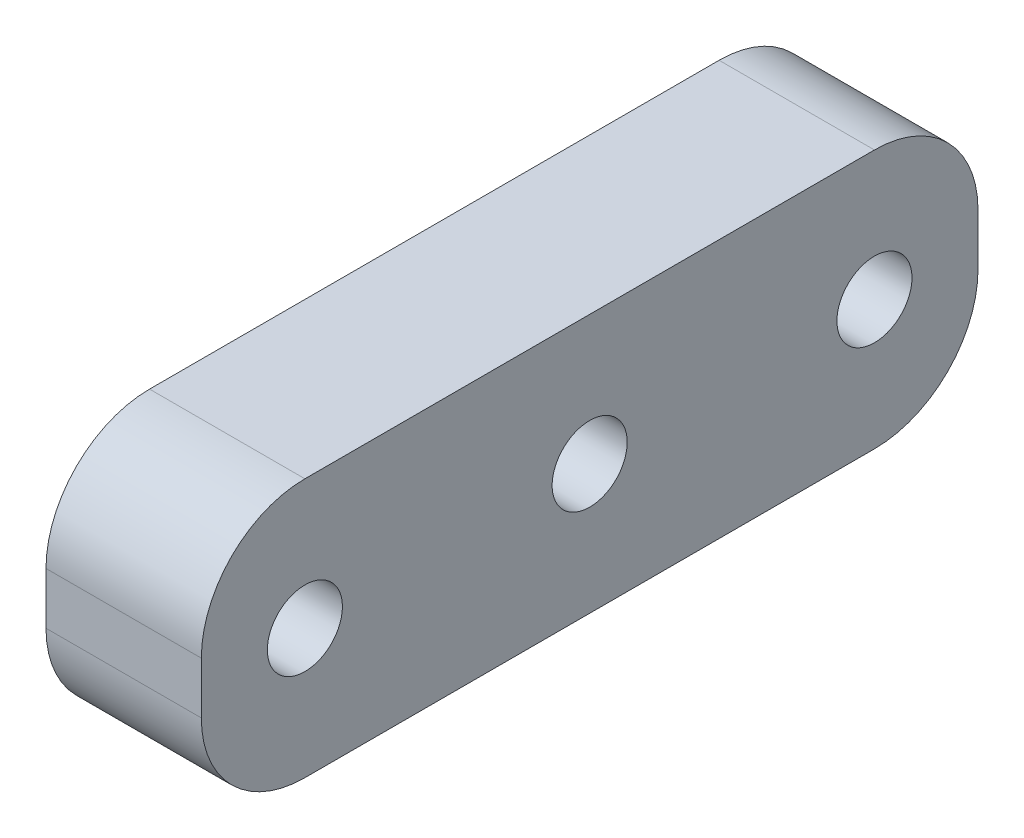
SolidWorks part; units mm, degrees
ref_plane "Front" through (0, 0, 0) normal (0, 0, 1) x (1, 0, 0)
ref_plane "Top" through (0, 0, 0) normal (0, 1, 0) x (1, 0, 0)
ref_plane "Right" through (0, 0, 0) normal (1, 0, 0) x (0, 0, -1)
sketch "Sketch1" plane through (0, 0, 0) normal (1, 0, 0) x (0, 0, -1)
  line L1 (0, 0) -> (30, 0)
  line L2 (0, 0) -> (0, -10)
  line L3 (0, -10) -> (30, -10)
  line L4 (30, 0) -> (30, -10)
  dimension "D1" = 10
  dimension "D2" = 30
extrude "Boss-Extrude1" add sketch "Sketch1" along normal blind 6
sketch "Sketch2" plane through (6, 0, 0) normal (1, 0, 0) x (0, 0, -1)
  line L0 (30, 0) -> (0, 0) construction
  line L1 (0, 0) -> (0, -10) construction
  line L2 (30, -10) -> (30, 0) construction
  circle A0 centre (4, -5) radius 1.45
  circle A1 centre (15, -5) radius 1.45
  circle A2 centre (26, -5) radius 1.45
  dimension "D1" = 2.9
  dimension "D2" = 2.9
  dimension "D3" = 2.9
  dimension "D4" = 5
  dimension "D5" = 5
  dimension "D6" = 5
  dimension "D7" = 4
  dimension "D8" = 4
  dimension "D9" = 15
extrude "Cut-Extrude1" cut sketch "Sketch2" against normal through all
fillet "Fillet1" radius 4 4 edges at (3, -10, -30) (3, 0, -30) (3, 0, 0) (3, -10, 0)
